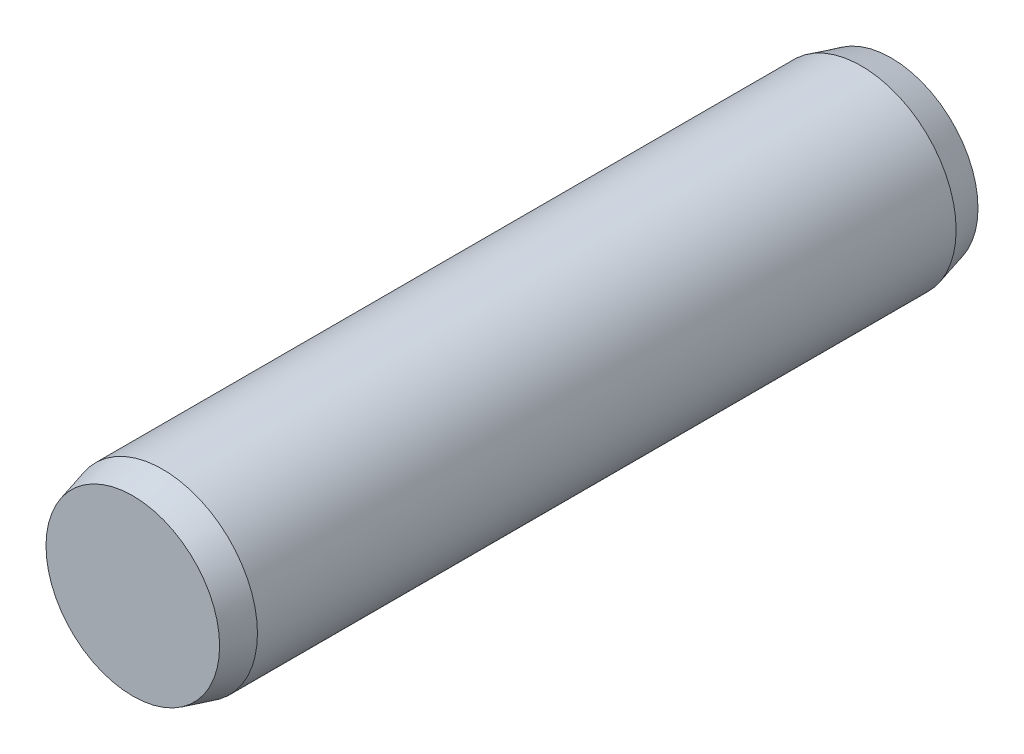
SolidWorks part; units mm, degrees
ref_plane "Front Plane" through (0, 0, 0) normal (0, 0, 1) x (1, 0, 0)
ref_plane "Top Plane" through (0, 0, 0) normal (0, 1, 0) x (1, 0, 0)
ref_plane "Right Plane" through (0, 0, 0) normal (1, 0, 0) x (0, 0, -1)
sketch "Sketch1" plane through (0, 0, 0) normal (1, 0, 0) x (0, 0, -1)
  line L0 (-8, 0) -> (8, 0)
  dimension "Length" = 16
sketch "Sketch2" plane through (0, 0, 0) normal (0, 0, 1) x (1, 0, 0)
  circle A0 centre (0, 0) radius 2
  dimension "Diameter" = 4
sketch "Sketch3" plane through (0, 0, 0) normal (1, 0, 0) x (0, 0, -1)
  line L0 (-8, 0) -> (-8, 1.8312)
  line L1 (-8, 1.8312) -> (-7.37, 2)
  line L2 (-7.37, 2) -> (7.37, 2)
  line L5 (8, 0) -> (-8, 0)
  line L6 (-8, 0) -> (8, 0) construction
  line L7 (-8, 0) -> (8, 0) construction
  line L8 (7.37, 2) -> (8, 1.8312)
  line L9 (8, 1.8312) -> (8, 0)
  point P0 (0, 2)
  dimension "D1" = 15
  dimension "Point Height" = 0.63
revolve "Revolve1" add sketch "Sketch3" angle 360 about L0
